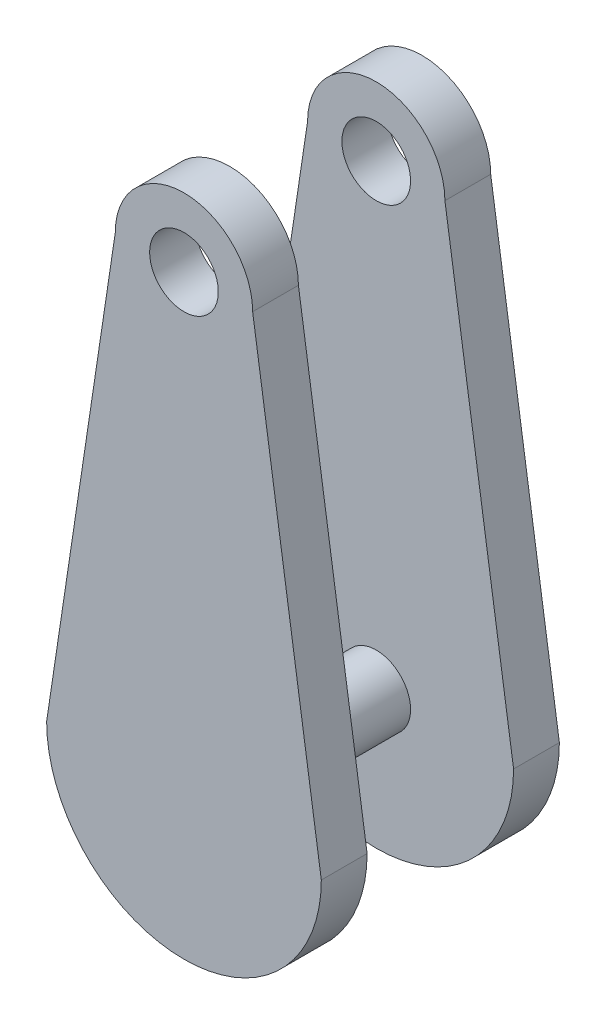
SolidWorks part; units mm, degrees
ref_plane "Front Plane" through (0, 0, 0) normal (0, 0, 1) x (1, 0, 0)
ref_plane "Top Plane" through (0, 0, 0) normal (0, 1, 0) x (1, 0, 0)
ref_plane "Right Plane" through (0, 0, 0) normal (1, 0, 0) x (0, 0, -1)
other "Center of Mass"
sketch "Sketch1" plane through (0, 0, 0) normal (0, 0, 1) x (1, 0, 0)
  line L0 (-15, 100) -> (-30, 0)
  line L1 (15, 100) -> (30, 0)
  arc A0 (-28.6797, 8.802) -> (28.6797, 8.802) centre (0, 0) ccw
  arc A1 (15, 100) -> (-15, 100) centre (0, 100) ccw
  circle A2 centre (0, 0) radius 7.5
  circle A3 centre (0, 100) radius 5
  dimension "D1" = 60
  dimension "D2" = 30
  dimension "D4" = 15
  dimension "D3" = 100
extrude "Boss-Extrude4" add sketch "Sketch1" along normal blind 10 contours L1 A1 L0 A0 A3 A2
ref_plane "Plane3" through (0, 0, 10) normal (0, 0, 1) x (1, 0, 0)
sketch "Sketch6" plane through (0, 0, 10) normal (0, 0, 1) x (1, 0, 0)
  circle A0 centre (0, 0) radius 7.5
extrude "Boss-Extrude5" add sketch "Sketch6" against normal blind 52
ref_plane "Plane4" through (0, 0, -16) normal (0, 0, 1) x (1, 0, 0)
mirror "Mirror1" about plane through (0, 0, -16) normal (0, 0, 1) of "Boss-Extrude4"
sketch "Sketch8" plane through (0, 0, 0) normal (0, 0, -1) x (-1, 0, 0)
  circle A0 centre (0, 0) radius 10
  circle A1 centre (0, 0) radius 7.5
extrude "Boss-Extrude7" add sketch "Sketch8" along normal blind 2
sketch "Sketch9" plane through (0, 0, -16) normal (0, 0, 1) x (1, 0, 0)
  line L0 (0, -50.9068) -> (0, 50.9068) construction
  line L1 (67.8727, 0) -> (-67.8727, 0) construction
  point P4 (0, 0)
  point P8 (0, 0)
sketch "Sketch10" plane through (0, 0, -42) normal (0, 0, -1) x (-1, 0, 0)
  circle A0 centre (0, 100) radius 7.5
extrude "Cut-Extrude2" cut sketch "Sketch10" against normal through all
